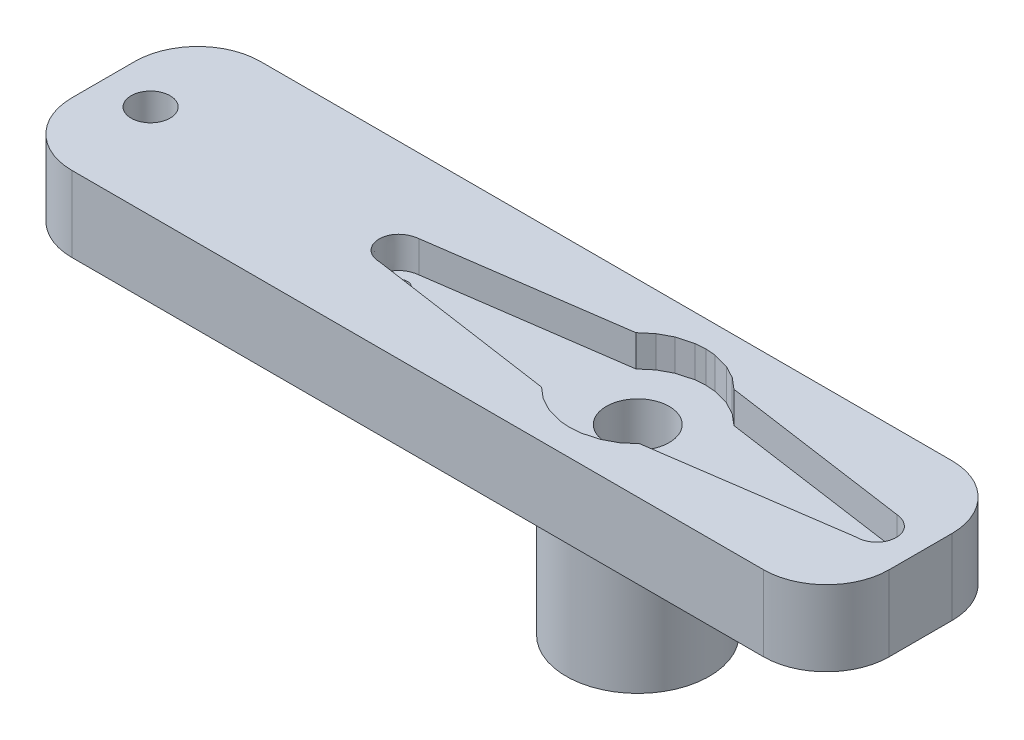
SolidWorks part; units mm, degrees
ref_plane "Plan de face" through (0, 0, 0) normal (0, 0, 1) x (1, 0, 0)
ref_plane "Plan de dessus" through (0, 0, 0) normal (0, 1, 0) x (1, 0, 0)
ref_plane "Plan de droite" through (0, 0, 0) normal (1, 0, 0) x (0, 0, -1)
sketch "Esquisse1" plane through (0, 0, 0) normal (0, 1, 0) x (1, 0, 0)
  line L1 (0, -55) -> (0, 55) construction
  line L2 (-55, 0) -> (55, 0) construction
  line L3 (-22.5, 7.5) -> (22.5, 7.5)
  line L4 (-22.5, -7.5) -> (22.5, -7.5)
  line L5 (22.5, -7.5) -> (22.5, 7.5)
  line L6 (-22.5, -7.5) -> (-22.5, 7.5)
  point P8 (0, 0)
  dimension "D1" = 15
  dimension "D2" = 45
extrude "Boss.-Extru.1" add sketch "Esquisse1" along normal blind 6
sketch "Esquisse2" plane through (0, 0, 0) normal (0, -1, 0) x (1, 0, 0)
  circle A0 centre (0, 0) radius 2.5
extrude "Enlèv. mat.-Extru.1" cut sketch "Esquisse2" against normal blind 6
sketch "Esquisse3" plane through (0, 6, 0) normal (0, 1, 0) x (1, 0, 0)
  line L0 (-55, 0) -> (55, 0) construction
  line L1 (19, -1.5617) -> (3.9, -3.75)
  line L2 (19, 1.6) -> (3.9, 3.75)
  line L3 (3.9, -3.75) -> (3.0319, -4.4831)
  line L4 (3.0319, -4.4831) -> (2.0397, -5.013)
  line L5 (2.0397, -5.013) -> (0.8046, -5.3519)
  line L6 (0.8046, -5.3519) -> (0, -5.412)
  line L7 (3.9, 3.75) -> (3.0319, 4.4831)
  line L8 (3.0319, 4.4831) -> (2.0397, 5.013)
  line L9 (2.0397, 5.013) -> (0.8046, 5.3519)
  line L10 (0.8046, 5.3519) -> (0, 5.412)
  line L11 (0, -55) -> (0, 55) construction
  line L12 (-0.8046, 5.3519) -> (0, 5.412)
  line L13 (-2.0397, 5.013) -> (-0.8046, 5.3519)
  line L14 (-3.0319, 4.4831) -> (-2.0397, 5.013)
  line L15 (-3.9, 3.75) -> (-3.0319, 4.4831)
  line L16 (-0.8046, -5.3519) -> (0, -5.412)
  line L17 (-2.0397, -5.013) -> (-0.8046, -5.3519)
  line L18 (-3.0319, -4.4831) -> (-2.0397, -5.013)
  line L19 (-3.9, -3.75) -> (-3.0319, -4.4831)
  line L20 (-19, 1.6) -> (-3.9, 3.75)
  line L21 (-19, -1.5617) -> (-3.9, -3.75)
  circle A0 centre (19, 0) radius 1.5617 construction
  circle A1 centre (0, 0) radius 5.412 construction
  circle A2 centre (-19, 0) radius 1.5617 construction
  spline S0 degree 3 poles (19, -1.5617) (19.5406, -1.5747) (20.3393, -1.095) (20.6517, 0.0475) (20.2936, 1.1588) (19.4777, 1.556) (19, 1.6) knots 0 0 0 0 0.329485 0.499359 0.699444 1 1 1 1
  spline S1 degree 3 poles (-19, -1.5617) (-19.5406, -1.5747) (-20.3393, -1.095) (-20.6517, 0.0475) (-20.2936, 1.1588) (-19.4777, 1.556) (-19, 1.6) knots 0 0 0 0 0.329485 0.499359 0.699444 1 1 1 1
  point P0 (3.9, -3.75)
  point P1 (19, 1.6)
  point P4 (3.9, 3.75)
  point P6 (19, -1.6)
  point P47 (-19, -1.6)
  point P48 (-3.9, 3.75)
  point P49 (-19, 1.6)
  point P50 (-3.9, -3.75)
  dimension "D1" = 3.9
  dimension "D2" = 7.5
  dimension "D3" = 15.1
  dimension "D4" = 3.2
sketch "Esquisse4" plane through (0, 0, 0) normal (0, -1, 0) x (1, 0, 0)
  line L0 (0, -55) -> (0, 55) construction
  circle A0 centre (19, 0) radius 0.7
  circle A1 centre (-19, 0) radius 0.7
  dimension "D1" = 19
extrude "Enlèv. mat.-Extru.2" cut sketch "Esquisse4" against normal blind 7
extrude "Enlèv. mat.-Extru.3" cut sketch "Esquisse3" against normal blind 2.5
sketch "Esquisse7" plane through (-22.5, 0, 0) normal (-1, 0, 0) x (0, 0, 1)
  line L0 (7.5, 6) -> (7.5, 0)
  line L1 (8.25, 0) -> (-8.25, 0) construction
  line L2 (7.5, 6) -> (7.5, 0) construction
  line L3 (7.5, 0) -> (-7.5, 0)
  line L4 (-7.5, 0) -> (-7.5, 6)
  line L5 (-7.5, 6) -> (7.5, 6)
extrude "Boss.-Extru.2" add sketch "Esquisse7" along normal blind 20
sketch "Esquisse8" plane through (0, 0, 0) normal (0, -1, 0) x (1, 0, 0)
  line L0 (3.3, 0) -> (-3.3, 0) construction
  circle A0 centre (-38.7394, 0) radius 1.55
  dimension "D1" = 3.1
extrude "Enlèv. mat.-Extru.4" cut sketch "Esquisse8" against normal blind 7.5
fillet "Congé1" radius 5 4 edges at (22.5, 3, -7.5) (22.5, 3, 7.5) (-42.5, 3, -7.5) (-42.5, 3, 7.5)
sketch "Esquisse9" plane through (0, 0, 0) normal (0, -1, 0) x (1, 0, 0)
  circle A0 centre (0, 0) radius 4.4
  circle A1 centre (0, 0) radius 5.6931
  dimension "D1" = 8.8
  dimension "D2" = 11.3861
extrude "Boss.-Extru.3" add sketch "Esquisse9" along normal blind 11
